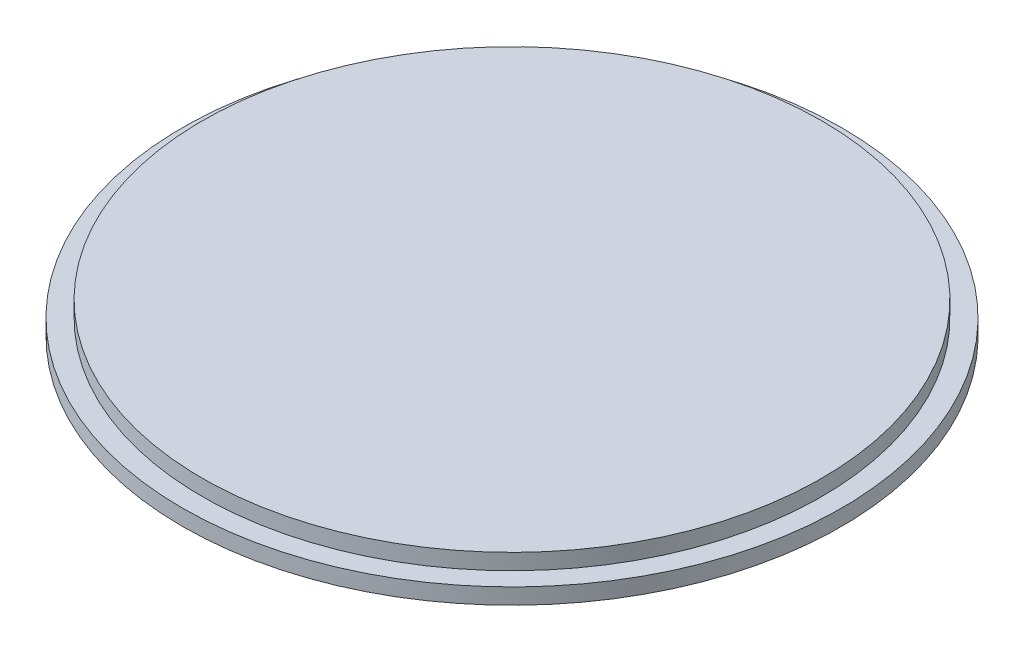
SolidWorks part; units mm, degrees
ref_plane "Front Plane" through (0, 0, 0) normal (0, 0, 1) x (1, 0, 0)
ref_plane "Top Plane" through (0, 0, 0) normal (0, 1, 0) x (1, 0, 0)
ref_plane "Right Plane" through (0, 0, 0) normal (1, 0, 0) x (0, 0, -1)
sketch "Sketch1" plane through (0, 0, 0) normal (0, 1, 0) x (1, 0, 0)
  circle A0 centre (0, 0) radius 49.403
  dimension "D1" = 98.806
extrude "Boss-Extrude1" add sketch "Sketch1" along normal blind 2.3813
sketch "Sketch2" plane through (0, 2.3813, 0) normal (0, 1, 0) x (1, 0, 0)
  circle A0 centre (0, 0) radius 46.4248
  dimension "D1" = 92.8497
extrude "Boss-Extrude2" add sketch "Sketch2" along normal blind 2.3813
